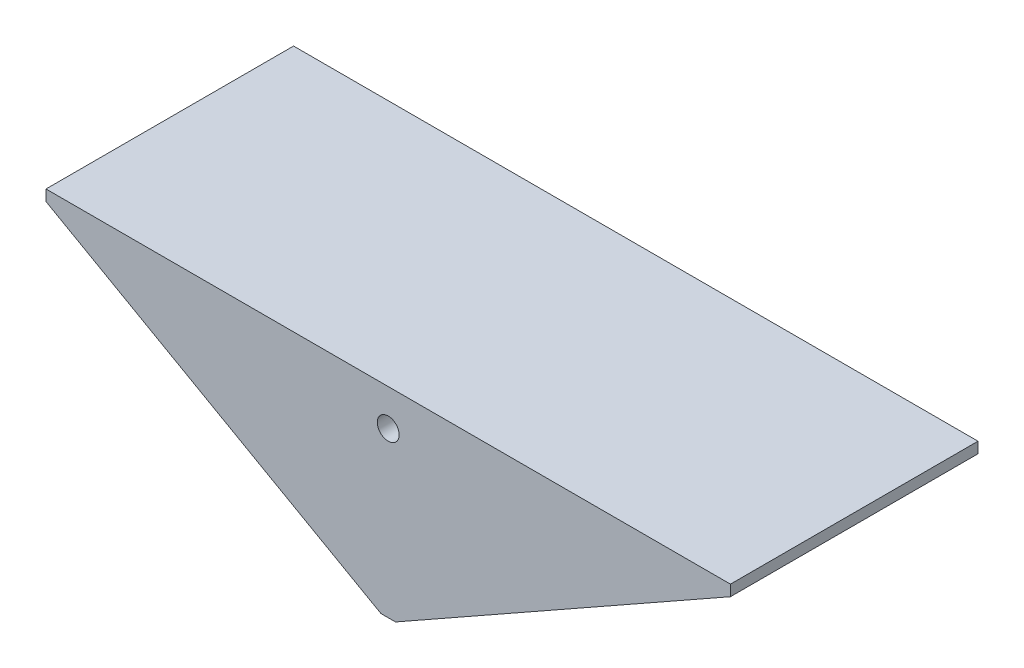
SolidWorks part; units mm, degrees
ref_plane "前视基准面" through (0, 0, 0) normal (0, 0, 1) x (1, 0, 0)
ref_plane "上视基准面" through (0, 0, 0) normal (0, 1, 0) x (1, 0, 0)
ref_plane "右视基准面" through (0, 0, 0) normal (1, 0, 0) x (0, 0, -1)
sketch "草图1" plane through (0, 0, 0) normal (0, 1, 0) x (1, 0, 0)
  line L1 (0, 0) -> (94, 0)
  line L2 (0, 0) -> (0, 34)
  line L3 (0, 34) -> (94, 34)
  line L4 (94, 0) -> (94, 34)
  dimension "D1" = 34
  dimension "D2" = 94
extrude "凸台-拉伸1" add sketch "草图1" along normal blind 2.5
sketch "草图2" plane through (0, 0, 0) normal (0, -1, 0) x (-1, 0, 0)
  line L0 (-2, 2) -> (-46, 2)
  line L1 (0, 0) -> (-94, 0)
  line L2 (0, 0) -> (0, 34)
  line L3 (0, 34) -> (-94, 34)
  line L4 (-94, 0) -> (-94, 34)
  line L5 (-92, 2) -> (-92, 32)
  line L6 (-2, 32) -> (-46, 32)
  line L7 (-2, 2) -> (-2, 32)
  line L8 (-48, 32) -> (-92, 32)
  line L9 (-48, 2) -> (-92, 2)
  line L10 (-46, 32) -> (-46, 2)
  line L12 (-48, 32) -> (-48, 2)
  line L14 (-2, 32) -> (-92, 32) construction
  line L15 (-2, 2) -> (-92, 2) construction
  dimension "D2" = 2
  dimension "D3" = 44
  dimension "D1" = 2
extrude "凸台-拉伸2" add sketch "草图2" along normal blind 25
sketch "草图6" plane through (0, 0, -34) normal (0, 0, -1) x (-1, 0, 0)
  line L0 (0, -25) -> (0, 1)
  line L1 (0, -25) -> (-46, -25)
  line L2 (0, -25) -> (-94, -25) construction
  line L3 (0, 2.5) -> (0, -25) construction
  line L4 (0, 1) -> (-46, -25)
  line L5 (-47, -25) -> (-47, 2.5) construction
  line L6 (-94, 2.5) -> (0, 2.5) construction
  line L7 (-94, -25) -> (-94, 1)
  line L8 (-94, 1) -> (-48, -25)
  line L9 (-94, -25) -> (-48, -25)
  dimension "D1" = 1.5
  dimension "D2" = 46
extrude "切除-拉伸1" cut sketch "草图6" against normal through all
sketch "草图7" plane through (0, 0, -34) normal (0, 0, -1) x (-1, 0, 0)
  line L0 (-94, 2.5) -> (0, 2.5) construction
  circle A0 centre (-47, -2.5) radius 5
  point P6 (-41.1496, 11.1748)
  dimension "D1" = 10
  dimension "D2" = 5
  dimension "D3" = 47
extrude "凸台-拉伸4" add sketch "草图7" against normal blind 34
sketch "草图8" plane through (0, 0, -34) normal (0, 0, -1) x (-1, 0, 0)
  line L0 (-94, 2.5) -> (0, 2.5) construction
  circle A0 centre (-47, -2.5) radius 1.5
  dimension "D1" = 3
  dimension "D2" = 5
extrude "切除-拉伸2" cut sketch "草图8" against normal through all
